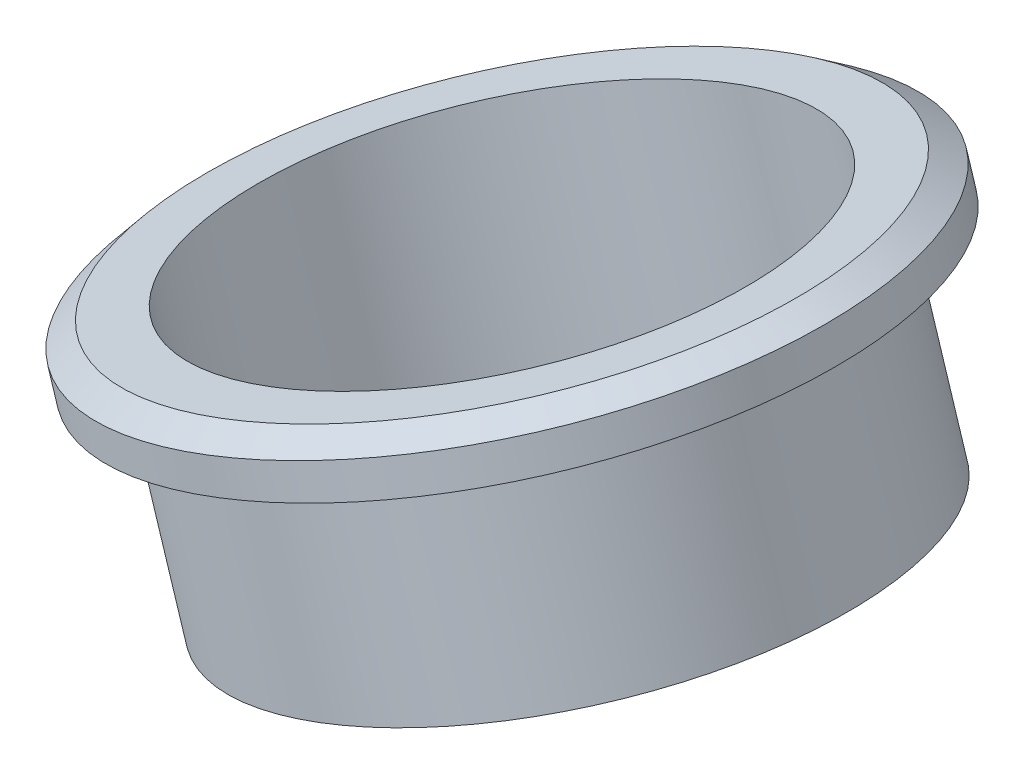
SolidWorks part; units mm, degrees
material "Acero aleado"
ref_plane "Alzado" through (0, 0, 0) normal (0, 0, 1) x (1, 0, 0)
ref_plane "Planta" through (0, 0, 0) normal (0, 1, 0) x (1, 0, 0)
ref_plane "Vista lateral" through (0, 0, 0) normal (1, 0, 0) x (0, 0, -1)
sketch "Sk_Cono" plane through (0, 0, 0) normal (0, 0, 1) x (1, 0, 0)
  line L0 (385.5004, 520.0564) -> (387.1217, 520.5676)
  line L1 (387.1217, 520.5676) -> (383.5131, 532.0121)
  line L2 (383.5131, 532.0121) -> (386.3743, 532.9143)
  line L3 (386.3743, 532.9143) -> (385.7729, 534.8217)
  line L4 (385.7729, 534.8217) -> (384.0416, 535.3244)
  line L5 (384.0416, 535.3244) -> (380.9897, 534.3621)
  line L6 (380.9897, 534.3621) -> (385.5004, 520.0564)
  line L7 (364.8943, 534.5297) -> (375.4193, 501.1497) construction
revolve "Cono" add sketch "Sk_Cono" angle 360 about L7
